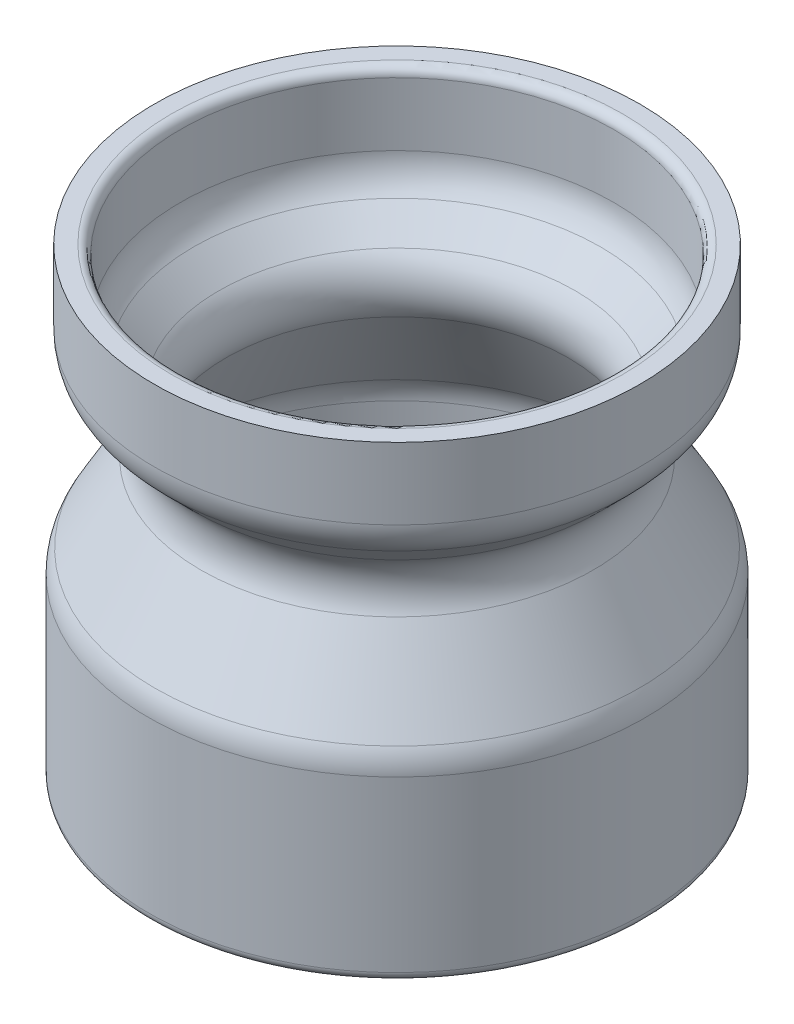
SolidWorks part; units mm, degrees
ref_plane "前基準面" through (0, 0, 0) normal (0, 0, 1) x (1, 0, 0)
ref_plane "上基準面" through (0, 0, 0) normal (0, 1, 0) x (1, 0, 0)
ref_plane "右基準面" through (0, 0, 0) normal (1, 0, 0) x (0, 0, -1)
sketch "草圖6" plane through (0, 0, 0) normal (0, 0, 1) x (1, 0, 0)
  line L0 (0, 0) -> (0, 60) construction
  line L1 (-2.5, 0) -> (-26.5, 0)
  line L2 (-27.5, 1) -> (-27.5, 19.7594)
  line L3 (-26.8301, 22.2594) -> (-21.7491, 31.06)
  line L4 (-22.5437, 37.0956) -> (-25.4374, 39.9893)
  line L5 (-26.9018, 43.5248) -> (-26.9018, 51.4537)
  line L6 (-19.7417, 37.122) -> (-22.5443, 39.9246)
  line L7 (-24.0088, 43.4602) -> (-24.0088, 50.4537)
  line L8 (-25.0088, 51.4537) -> (-26.9018, 51.4537)
  line L9 (-18.9471, 31.0865) -> (-24.8301, 20.8969)
  line L10 (-25.5, 18.3969) -> (-25.5, 3)
  line L11 (-24.5, 2) -> (-2.5, 2)
  line L12 (-2.5, 2) -> (-2.5, 0)
  line L13 (-2.5, 4) -> (-2.5, 6)
  line L14 (-2.5, 6) -> (-24, 6)
  line L15 (-24.5, 5.5) -> (-24.5, 4.5)
  line L16 (-24, 4) -> (-2.5, 4)
  arc A0 (-22.5443, 39.9246) -> (-24.0088, 43.4602) centre (-19.0088, 43.4602) cw
  arc A1 (-25.4374, 39.9893) -> (-26.9018, 43.5248) centre (-21.9018, 43.5248) cw
  arc A2 (-27.5, 19.7594) -> (-26.8301, 22.2594) centre (-22.5, 19.7594) cw
  arc A3 (-24.8301, 20.8969) -> (-25.5, 18.3969) centre (-20.5, 18.3969) ccw
  arc A4 (-19.7417, 37.122) -> (-18.9471, 31.0865) centre (-23.2773, 33.5865) cw
  arc A5 (-21.7491, 31.06) -> (-22.5437, 37.0956) centre (-26.0792, 33.56) ccw
  arc A6 (-24.0088, 50.4537) -> (-25.0088, 51.4537) centre (-25.0088, 50.4537) ccw
  arc A7 (-25.5, 3) -> (-24.5, 2) centre (-24.5, 3) ccw
  arc A8 (-26.5, 0) -> (-27.5, 1) centre (-26.5, 1) cw
  arc A9 (-24.5, 4.5) -> (-24, 4) centre (-24, 4.5) ccw
  arc A10 (-24, 6) -> (-24.5, 5.5) centre (-24, 5.5) ccw
  point P23 (-26.9018, 41.4537)
  point P32 (-19.8308, 34.3826)
  point P35 (-24.0088, 51.4537)
  point P40 (-27.5, 0)
  dimension "D14" = 5
  dimension "D15" = 1
  dimension "D16" = 0.5
  dimension "D1" = 2.5
  dimension "D2" = 25
  dimension "D3" = 10
  dimension "D4" = 60
  dimension "D5" = 2
  dimension "D6" = 2
  dimension "D7" = 150
  dimension "D8" = 10
  dimension "D9" = 2
  dimension "D10" = 2.893
  dimension "D11" = 1
  dimension "D12" = 2
  dimension "D13" = 2
revolve "旋轉1" add sketch "草圖6" angle 360 about L0
sketch "草圖7" plane through (0, 6, 0) normal (0, 1, 0) x (1, 0, 0)
  line L0 (15, -3.9) -> (15, 4.1) construction
  line L1 (13, -3.9) -> (13, 4.1)
  line L2 (17, -3.9) -> (17, 4.1)
  arc A0 (13, -3.9) -> (17, -3.9) centre (15, -3.9) ccw
  arc A1 (17, 4.1) -> (13, 4.1) centre (15, 4.1) ccw
  point P2 (15, 0.1)
  point P7 (0, 0)
  point P8 (0, 0)
  point P9 (0, 0)
extrude "除料-伸長2" cut sketch "草圖7" against normal up to next
sketch "草圖8" plane through (0, 0, 0) normal (0, -1, 0) x (1, 0, 0)
  line L0 (-15, -3.9) -> (-15, 4.1) construction
  line L1 (-17, -3.9) -> (-17, 4.1)
  line L2 (-13, -3.9) -> (-13, 4.1)
  arc A0 (-17, -3.9) -> (-13, -3.9) centre (-15, -3.9) ccw
  arc A1 (-13, 4.1) -> (-17, 4.1) centre (-15, 4.1) ccw
  point P1 (0, 0)
  point P3 (-15, 0.1)
  point P8 (0, 0)
extrude "除料-伸長4" cut sketch "草圖8" against normal up to next
